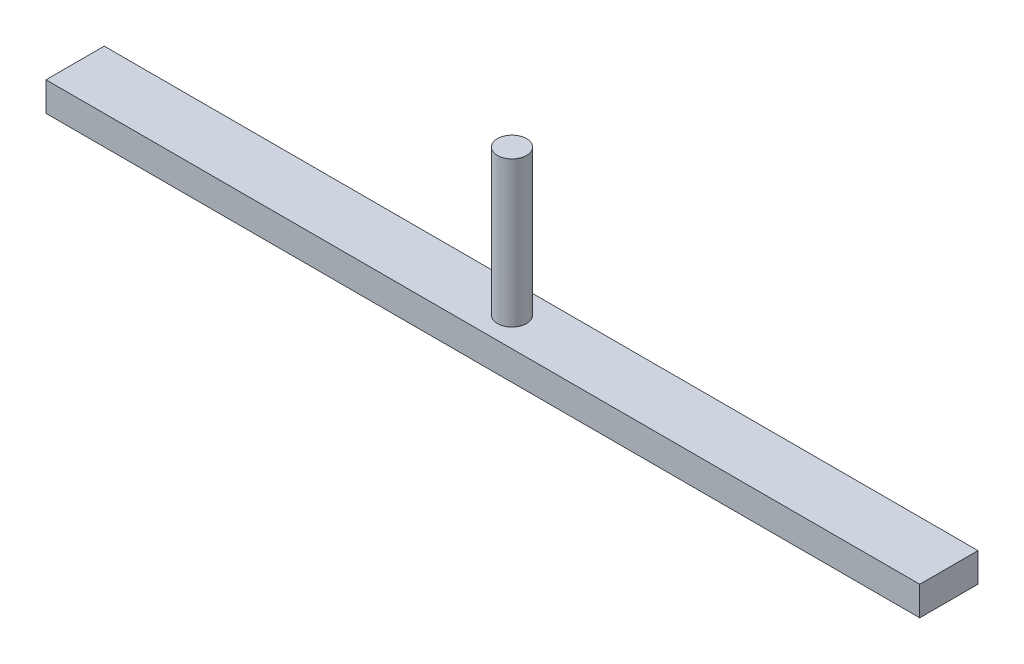
SolidWorks part; units mm, degrees
ref_plane "Front Plane" through (0, 0, 0) normal (0, 0, 1) x (1, 0, 0)
ref_plane "Top Plane" through (0, 0, 0) normal (0, 1, 0) x (1, 0, 0)
ref_plane "Right Plane" through (0, 0, 0) normal (1, 0, 0) x (0, 0, -1)
sketch "Sketch1" plane through (0, 0, 0) normal (0, 1, 0) x (1, 0, 0)
  line L0 (-75, 10.5397) -> (75, 10.5397) construction
  line L1 (-75, 5.5397) -> (75, 5.5397)
  line L2 (-75, 5.5397) -> (-75, 15.5397)
  line L3 (-75, 15.5397) -> (75, 15.5397)
  line L4 (75, 5.5397) -> (75, 15.5397)
  line L5 (0, 5.5397) -> (0, 15.5397) construction
  point P0 (0, 0)
  dimension "D1" = 150
  dimension "D2" = 10
extrude "Boss-Extrude2" add sketch "Sketch1" along normal blind 5
sketch "Sketch3" plane through (0, 5, 0) normal (0, 1, 0) x (1, 0, 0)
  line L0 (-75, 10.5397) -> (75, 10.5397) construction
  line L1 (-75, 15.5397) -> (-75, 5.5397) construction
  line L2 (75, 5.5397) -> (75, 15.5397) construction
  line L3 (0, 5.5397) -> (0, 15.5397) construction
  line L4 (-75, 5.5397) -> (75, 5.5397) construction
  line L5 (75, 15.5397) -> (-75, 15.5397) construction
  circle A0 centre (0, 10.5397) radius 2.5
  dimension "D1" = 5
extrude "Boss-Extrude4" add sketch "Sketch3" along normal blind 25 contours A0
